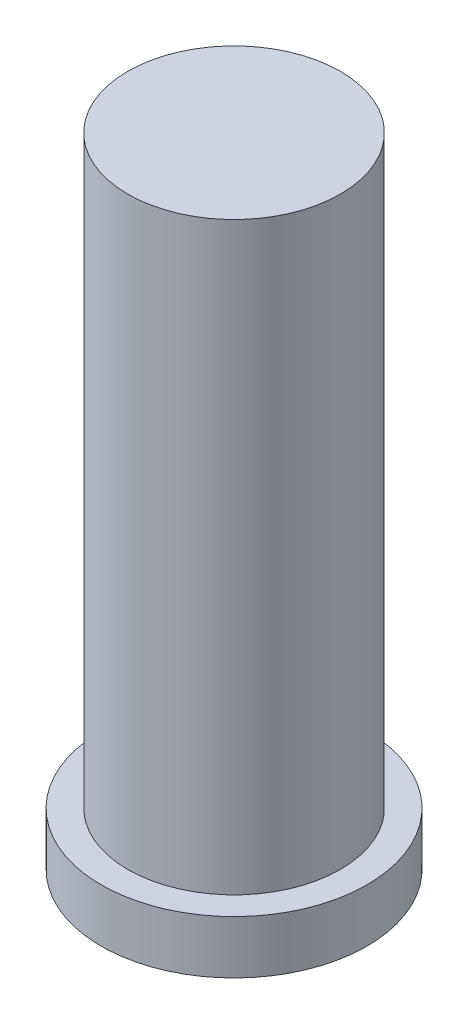
SolidWorks part; units mm, degrees
ref_plane "Front Plane" through (0, 0, 0) normal (0, 0, 1) x (1, 0, 0)
ref_plane "Top Plane" through (0, 0, 0) normal (0, 1, 0) x (1, 0, 0)
ref_plane "Right Plane" through (0, 0, 0) normal (1, 0, 0) x (0, 0, -1)
sketch "Sketch1" plane through (0, 0, 0) normal (0, 1, 0) x (1, 0, 0)
  circle A0 centre (0, 0) radius 4
  dimension "D1" = 8
extrude "Boss-Extrude1" add sketch "Sketch1" along normal blind 22
sketch "Sketch2" plane through (0, 0, 0) normal (0, -1, 0) x (1, 0, 0)
  circle A0 centre (0, 0) radius 5
  dimension "D1" = 10
extrude "Boss-Extrude3" add sketch "Sketch2" along normal blind 2
